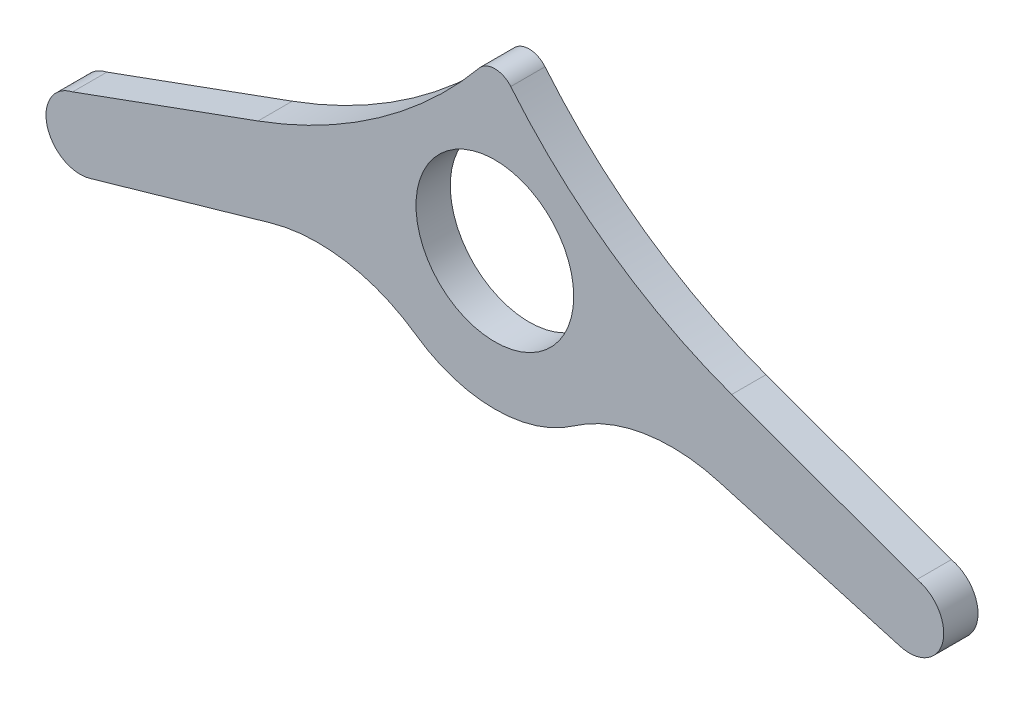
SolidWorks part; units mm, degrees
ref_plane "Płaszczyzna przednia" through (0, 0, 0) normal (0, 0, 1) x (1, 0, 0)
ref_plane "Płaszczyzna górna" through (0, 0, 0) normal (0, 1, 0) x (1, 0, 0)
ref_plane "Płaszczyzna prawa" through (0, 0, 0) normal (1, 0, 0) x (0, 0, -1)
sketch "Szkic1" plane through (0, 0, 0) normal (0, 0, 1) x (1, 0, 0)
  line L0 (0, -21.7767) -> (0, 0) construction
  line L1 (0, 0) -> (105.2688, 0) construction
  line L2 (105.2688, 0) -> (0, 0) construction
  line L3 (0, 0) -> (60.0789, -17.2273) construction
  line L4 (61.5756, -10.7097) -> (34.541, -0.8699)
  line L5 (32.7066, -12.827) -> (59.0806, -20.3896)
  line L6 (-61.5756, -10.7097) -> (-34.541, -0.8699)
  line L7 (-32.7066, -12.827) -> (-59.0806, -20.3896)
  circle A0 centre (0, 0) radius 11.5
  arc A1 (-11.4736, -16.3816) -> (11.4736, -16.3816) centre (0, 0) ccw
  circle A2 centre (0, 0) radius 62.5 construction
  arc A3 (59.0806, -20.3896) -> (61.5756, -10.7097) centre (60.4587, -15.5833) ccw
  arc A4 (32.7066, -12.827) -> (11.4736, -16.3816) centre (25.8156, -36.8586) ccw
  arc A5 (-2.3151, 21.908) -> (2.3151, 21.908) centre (0, 20) cw
  arc A6 (-59.0806, -20.3896) -> (-61.5756, -10.7097) centre (-60.4587, -15.5833) cw
  arc A7 (-32.7066, -12.827) -> (-11.4736, -16.3816) centre (-25.8156, -36.8586) cw
  arc A8 (2.3151, 21.908) -> (34.541, -0.8699) centre (60.1925, 69.6071) ccw
  arc A9 (-2.3151, 21.908) -> (-34.541, -0.8699) centre (-60.1925, 69.6071) cw
  arc A10 (20, 0) -> (18.6811, 7.1427) centre (0, 0) ccw
  point P25 (0, 23)
  point P30 (0, 0)
  dimension "D1" = 23
  dimension "D2" = 40
  dimension "D3" = 125
  dimension "D5" = 5
  dimension "D6" = 25
  dimension "D7" = 3
  dimension "D8" = 4
  dimension "D9" = 75
  dimension "D4" = 16
  dimension "D10" = 27.4369
extrude "Dodanie-wyciągnięcie1" add sketch "Szkic1" along normal blind 5
